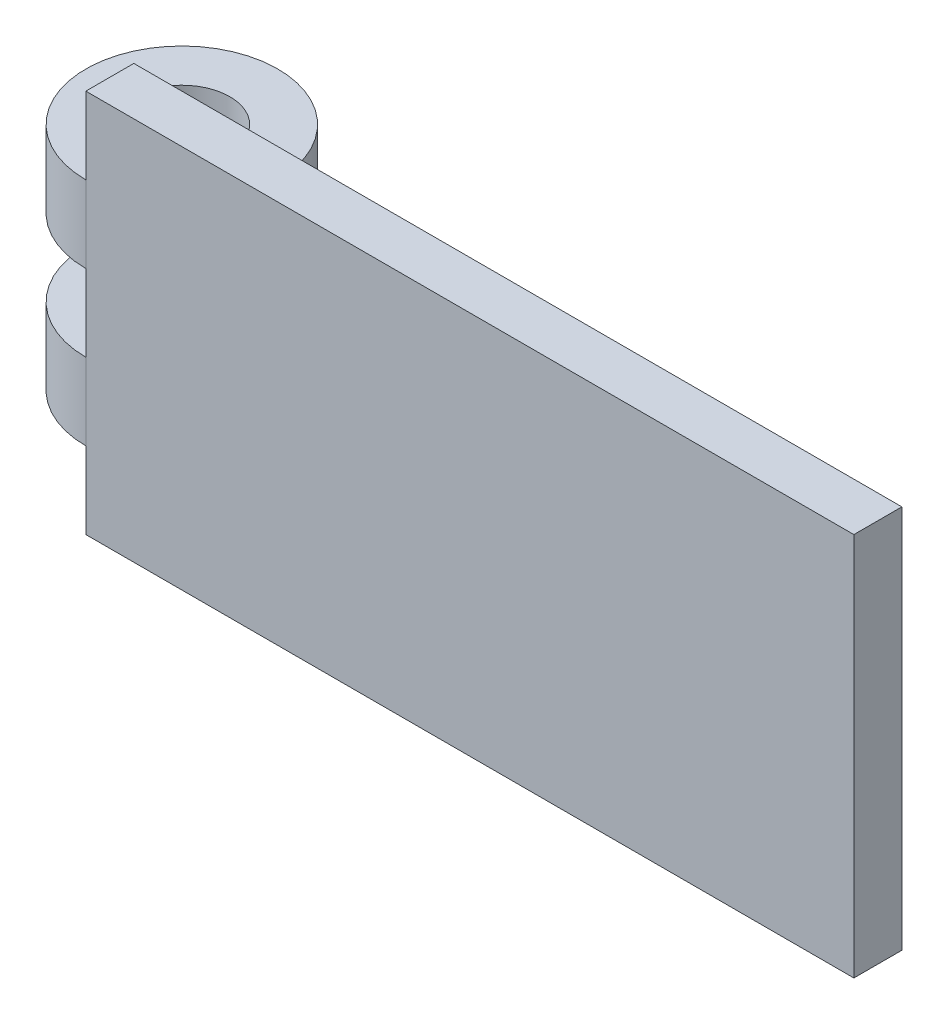
SolidWorks part; units mm, degrees
ref_plane "Front Plane" through (0, 0, 0) normal (0, 0, 1) x (1, 0, 0)
ref_plane "Top Plane" through (0, 0, 0) normal (0, 1, 0) x (1, 0, 0)
ref_plane "Right Plane" through (0, 0, 0) normal (1, 0, 0) x (0, 0, -1)
sketch "Sketch1" plane through (0, 0, 0) normal (0, 1, 0) x (1, 0, 0)
  line L1 (0, 0) -> (50.8, 0)
  line L2 (0, 0) -> (0, 3.175)
  line L3 (0, 3.175) -> (50.8, 3.175)
  line L4 (50.8, 0) -> (50.8, 3.175)
  dimension "D1" = 50.8
  dimension "D2" = 3.175
extrude "Boss-Extrude1" add sketch "Sketch1" along normal blind 25.4
ref_plane "Plane1" through (0, 20.32, 0) normal (0, 1, 0) x (1, 0, 0)
sketch "Sketch2" plane through (0, 20.32, 0) normal (0, 1, 0) x (1, 0, 0)
  line L0 (0, 3.175) -> (0, 0) construction
  circle A0 centre (0, 6.35) radius 6.35
  circle A1 centre (0, 6.35) radius 3.175
  dimension "D1" = 12.7
extrude "Boss-Extrude2" add sketch "Sketch2" against normal blind 5.08
pattern_linear "LPattern1" count 2 spacing 10.16 along (0, -1, 0) of "Boss-Extrude2"
